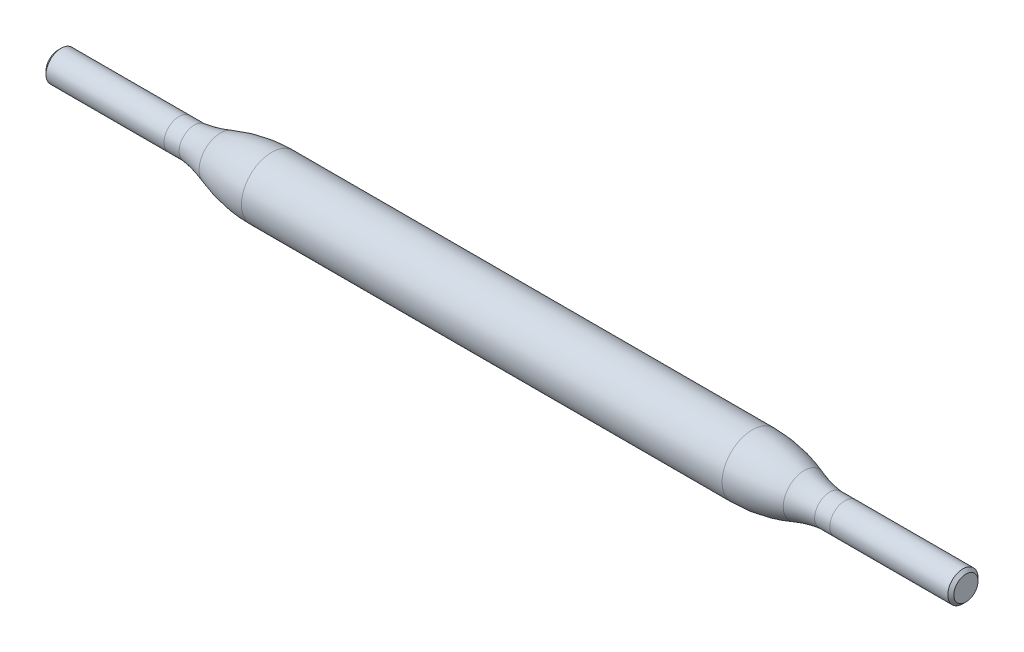
SolidWorks part; units mm, degrees
ref_plane "Front Plane" through (0, 0, 0) normal (0, 0, 1) x (1, 0, 0)
ref_plane "Top Plane" through (0, 0, 0) normal (0, 1, 0) x (1, 0, 0)
ref_plane "Right Plane" through (0, 0, 0) normal (1, 0, 0) x (0, 0, -1)
sketch "Sketch1" plane through (0, 0, 0) normal (0, 0, 1) x (1, 0, 0)
  line L0 (-30, 0) -> (30, 0)
  line L1 (30, 0) -> (30, 1)
  line L2 (-30, 0) -> (-30, 1)
  line L3 (-30, 1) -> (-21, 1)
  line L4 (-15.8844, 2) -> (15.8844, 2)
  line L5 (30, 1) -> (21, 1)
  arc A0 (-21, 1) -> (-19.2721, 1.4087) centre (-21.9306, 8.7919) ccw
  arc A1 (19.317, 1.3924) -> (21, 1) centre (21.7674, 8.0968) ccw
  arc A2 (15.8844, 2) -> (19.317, 1.3924) centre (15.8844, -8) cw
  arc A3 (-15.8844, 2) -> (-19.2721, 1.4087) centre (-15.8844, -8) ccw
  point P6 (0, 0)
  point P8 (0, 2)
  point P17 (-18, 2)
  dimension "D7" = 10
  dimension "D1" = 60
  dimension "D2" = 1
  dimension "D3" = 9
  dimension "D4" = 9
  dimension "D5" = 2
  dimension "D6" = 3
revolve "Revolve1" add sketch "Sketch1" angle 360 about L0
sketch "Sketch2" plane through (0, 0, 0) normal (0, 0, 1) x (1, 0, 0)
  line L0 (-22, 3.6427) -> (-22, -2.6111)
  line L1 (22, 6.0281) -> (22, -2.6111)
  line L2 (-30, 1) -> (-30, -1) construction
  line L3 (30, -1) -> (30, 1) construction
  dimension "D1" = 8
  dimension "D2" = 8
split line "Split Line1"
chamfer "Chamfer1" distance 0.2 angle 45 2 edges at (-30, -1, 0) (30, -1, 0)
